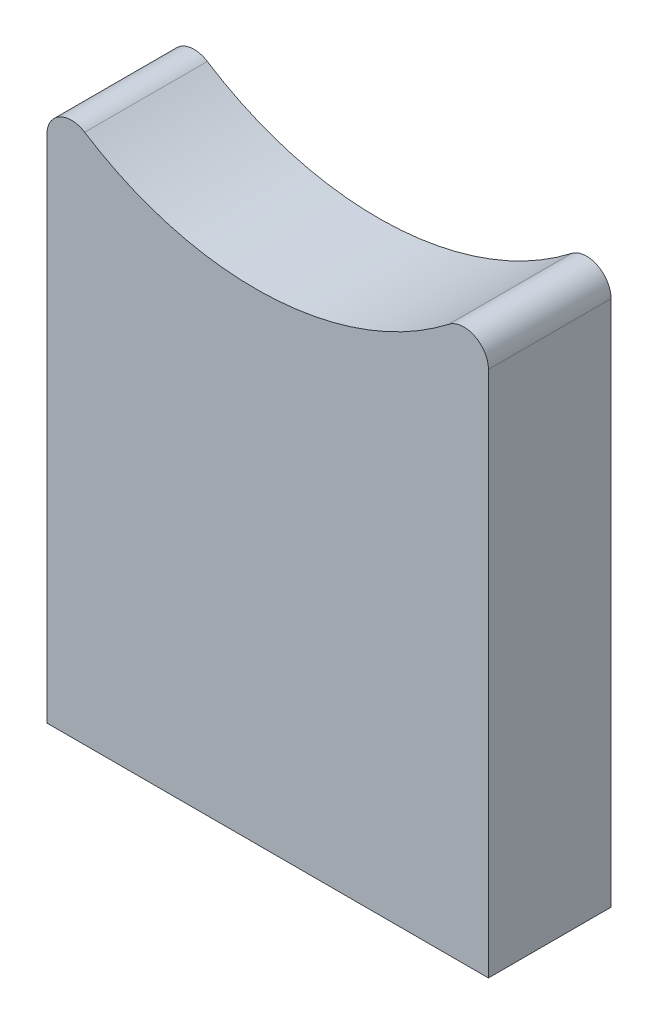
SolidWorks part; units mm, degrees
material "PET"
ref_plane "Piano frontale" through (0, 0, 0) normal (0, 0, 1) x (1, 0, 0)
ref_plane "Piano superiore" through (0, 0, 0) normal (0, 1, 0) x (1, 0, 0)
ref_plane "Piano destro" through (0, 0, 0) normal (1, 0, 0) x (0, 0, -1)
sketch "Schizzo1" plane through (0, 0, 0) normal (0, 0, 1) x (1, 0, 0)
  line L0 (-18, 0) -> (-18, 45.5767)
  line L5 (18, 47.5113) -> (18, 0)
  line L6 (18, 0) -> (-18, 0)
  line L7 (0, 0) -> (0, 35) construction
  arc A0 (-18, 45.5767) -> (18, 47.5113) centre (-0.9898, 64.9637) ccw
  point P1 (-18, 45.5767)
  point P3 (18, 47.8971)
  point P6 (-17.691, 45.6872)
  point P8 (0, 0)
  point P10 (18, 47.5113)
  dimension "D2" = 36
  dimension "D4" = 35
extrude "Estrusione-Estrusione1" add sketch "Schizzo1" along normal blind 10
fillet "Raccordo1" radius 2 2 edges at (18, 47.5113, 5) (-18, 45.5767, 5)
